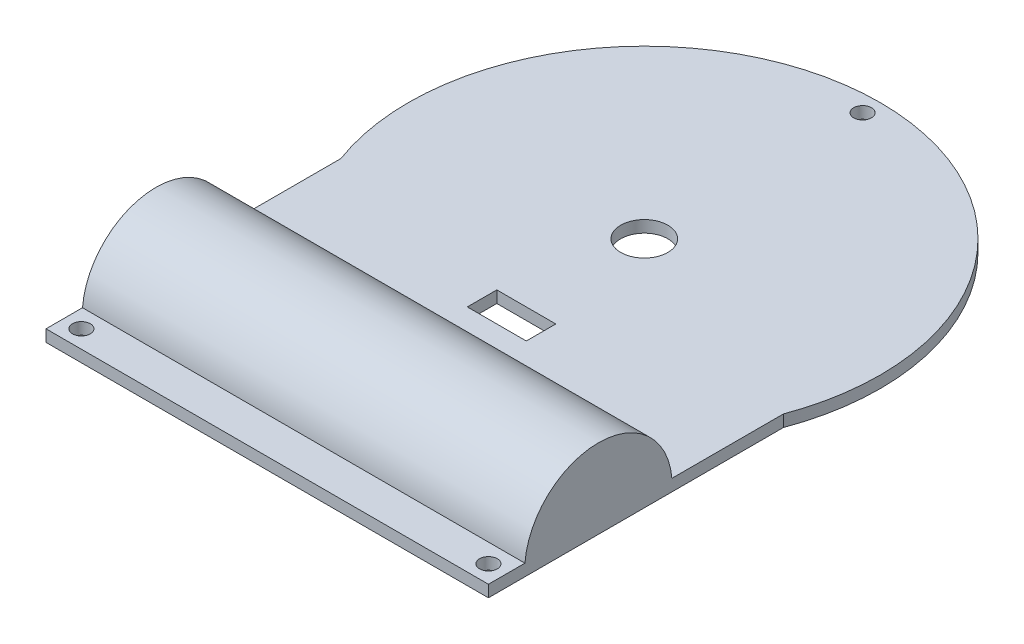
SolidWorks part; units mm, degrees
ref_plane "Front Plane" through (0, 0, 0) normal (0, 0, 1) x (1, 0, 0)
ref_plane "Top Plane" through (0, 0, 0) normal (0, 1, 0) x (1, 0, 0)
ref_plane "Right Plane" through (0, 0, 0) normal (1, 0, 0) x (0, 0, -1)
sketch "Sketch1" plane through (0, 0, 0) normal (0, 1, 0) x (1, 0, 0)
  line L1 (-37.5, -63.9194) -> (37.5, -63.9194)
  line L2 (-37.5, -63.9194) -> (-37.5, -13.9194)
  line L4 (37.5, -63.9194) -> (37.5, -13.9194)
  arc A0 (37.5, -13.9194) -> (-37.5, -13.9194) centre (0, 0) ccw
  dimension "D1" = 80
extrude "Boss-Extrude1" add sketch "Sketch1" along normal blind 2
sketch "Sketch2" plane through (0, 2, 0) normal (0, 1, 0) x (1, 0, 0)
  circle A0 centre (0, 0) radius 4
  dimension "D1" = 8
extrude "Cut-Extrude1" cut sketch "Sketch2" against normal blind 2
sketch "Sketch3" plane through (0, 2, 0) normal (0, 1, 0) x (1, 0, 0)
  line L1 (-5, -20) -> (5, -20)
  line L2 (-5, -20) -> (-5, -25)
  line L3 (-5, -25) -> (5, -25)
  line L4 (5, -20) -> (5, -25)
  circle A0 centre (0, 0) radius 4 construction
  point P4 (0, -20)
  dimension "D3" = 20
  dimension "D1" = 5
  dimension "D2" = 10
extrude "Cut-Extrude2" cut sketch "Sketch3" against normal blind 10
sketch "Sketch7" plane through (0, 2, 0) normal (0, 1, 0) x (1, 0, 0)
  line L1 (-37.5, -63.9194) -> (-31.5, -63.9194)
  line L2 (-37.5, -63.9194) -> (-37.5, -57.9194)
  line L3 (-37.5, -57.9194) -> (-31.5, -57.9194)
  line L4 (-31.5, -63.9194) -> (-31.5, -57.9194)
  line L5 (37.5, -63.9194) -> (31.5, -63.9194)
  line L6 (37.5, -63.9194) -> (37.5, -57.9194)
  line L7 (37.5, -57.9194) -> (31.5, -57.9194)
  line L8 (31.5, -63.9194) -> (31.5, -57.9194)
  line L9 (-3, 40) -> (3, 40)
  line L10 (-3, 40) -> (-3, 34)
  line L11 (-3, 34) -> (3, 34)
  line L12 (3, 40) -> (3, 34)
  circle A0 centre (-34.5, -60.9194) radius 1.5
  circle A1 centre (34.5, -60.9194) radius 1.5
  circle A2 centre (0, 37) radius 1.5
  point P21 (-34.5, -57.9194)
  point P22 (-31.5, -60.9194)
  point P24 (34.5, -57.9194)
  point P25 (31.5, -60.9194)
  point P26 (0, 34)
  point P30 (-3, 37)
  dimension "D1" = 3
  dimension "D2" = 3
  dimension "D3" = 3
  dimension "D4" = 6
  dimension "D5" = 6
  dimension "D6" = 6
  dimension "D7" = 6
  dimension "D8" = 6
  dimension "D9" = 6
extrude "Cut-Extrude3" cut sketch "Sketch7" against normal blind 10 contours A2 | A0 | A1
sketch "Sketch8" plane through (-37.5, 0, 0) normal (-1, 0, 0) x (0, 0, 1)
  circle A0 centre (45.2788, 0.9499) radius 10.5
  dimension "D1" = 21
extrude "Cut-Extrude4" cut sketch "Sketch8" against normal through all
sketch "Sketch9" plane through (-37.5, 0, 0) normal (-1, 0, 0) x (0, 0, 1)
  line L0 (32.815, 0) -> (34.8219, 0)
  line L1 (13.9194, 0) -> (34.8219, 0) construction
  line L2 (55.7358, 0) -> (57.7427, 0)
  arc A0 (55.7358, 0) -> (34.8219, 0) centre (45.2788, 0.9499) ccw
  arc A1 (57.7427, 0) -> (32.815, 0) centre (45.2788, 0.9499) ccw
  dimension "D2" = 2
extrude "Boss-Extrude2" add sketch "Sketch9" against normal up to surface (75 mm away) up to face at (37.5, 1.0001, 24.3611)
sketch "Sketch10" plane through (-37.5, 0, 0) normal (-1, 0, 0) x (0, 0, 1)
  line L0 (32.815, 0) -> (57.7427, 0)
  line L1 (13.9194, 0) -> (34.8219, 0) construction
  line L2 (55.7358, 0) -> (63.9194, 0) construction
  arc A0 (57.7427, 0) -> (32.815, 0) centre (45.2788, 0.9499) ccw
extrude "Boss-Extrude3" add sketch "Sketch10" against normal blind 2
sketch "Sketch11" plane through (37.5, 0, 0) normal (1, 0, 0) x (0, 0, -1)
  line L0 (-57.7427, 0) -> (-32.815, 0)
  line L1 (-63.9194, 0) -> (-55.7358, 0) construction
  arc A0 (-32.815, 0) -> (-57.7427, 0) centre (-45.2788, 0.9499) ccw
extrude "Boss-Extrude4" add sketch "Sketch11" against normal blind 2 contours A0 L0
